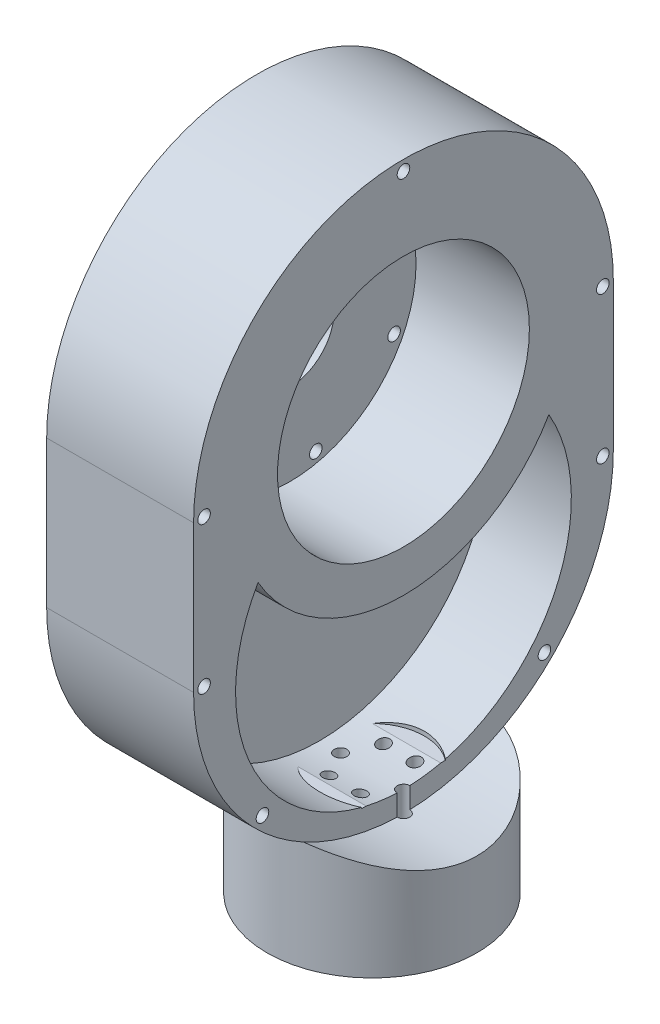
SolidWorks part; units mm, degrees
material "ABS"
ref_plane "Alzado" through (0, 0, 0) normal (0, 0, 1) x (1, 0, 0)
ref_plane "Planta" through (0, 0, 0) normal (0, 1, 0) x (1, 0, 0)
ref_plane "Vista lateral" through (0, 0, 0) normal (1, 0, 0) x (0, 0, -1)
sketch "Croquis3" plane through (0, 0, 0) normal (1, 0, 0) x (0, 0, -1)
  line L0 (-50, 105) -> (-50, 70)
  line L1 (50, 70) -> (50, 105)
  arc A0 (50, 105) -> (-50, 105) centre (0, 105) ccw
  arc A1 (-50, 70) -> (50, 70) centre (0, 70) ccw
  dimension "D1" = 100
  dimension "D3" = 35
  dimension "D4" = 70
extrude "Saliente-Extruir3" add sketch "Croquis3" along normal mid plane 55
sketch "Croquis2" plane through (0, 0, 0) normal (0, 1, 0) x (1, 0, 0)
  circle A0 centre (0, 0) radius 25
  dimension "D1" = 50
extrude "Saliente-Extruir4" add sketch "Croquis2" along normal up to next
sketch "Croquis5" plane through (-27.5, 0, 0) normal (-1, 0, 0) x (0, 0, 1)
  circle A0 centre (0, 105) radius 45
  circle A1 centre (0, 105) radius 32.5
  dimension "D1" = 90
  dimension "D2" = 65
extrude "Cortar-Extruir2" cut sketch "Croquis5" against normal blind 2.5
sketch "Croquis6" plane through (-27.5, 0, 0) normal (-1, 0, 0) x (0, 0, 1)
  circle A0 centre (0, 105) radius 10.5
  dimension "D1" = 21
extrude "Cortar-Extruir3" cut sketch "Croquis6" against normal through all
sketch "Croquis7" plane through (27.5, 0, 0) normal (1, 0, 0) x (0, 0, -1)
  line L2 (-50, 105) -> (-50, 70)
  line L3 (50, 70) -> (50, 105)
  line L4 (-50, 105) -> (-50, 70)
  line L5 (50, 70) -> (50, 105)
  arc A2 (50, 105) -> (-50, 105) centre (0, 105) ccw
  arc A3 (-50, 70) -> (50, 70) centre (0, 70) ccw
  arc A4 (50, 105) -> (-50, 105) centre (0, 105) ccw
  arc A5 (-50, 70) -> (50, 70) centre (0, 70) ccw
  dimension "D1" = 0
extrude "Cortar-Extruir4" cut sketch "Croquis7" against normal blind 20
sketch "Croquis8" plane through (7.5, 0, 0) normal (1, 0, 0) x (0, 0, -1)
  circle A0 centre (0, 105) radius 30
  dimension "D1" = 60
extrude "Cortar-Extruir5" cut sketch "Croquis8" against normal blind 27
sketch "Croquis9" plane through (0, 0, 0) normal (0, -1, 0) x (1, 0, 0)
  circle A6 centre (0, 0) radius 7.5 construction
  circle A7 centre (7.5, 0) radius 1.5
  circle A8 centre (3.75, -6.4952) radius 1.5
  circle A9 centre (-3.75, -6.4952) radius 1.5
  circle A10 centre (-7.5, 0) radius 1.5
  circle A11 centre (-3.75, 6.4952) radius 1.5
  circle A12 centre (3.75, 6.4952) radius 1.5
  point P17 (0, 0)
  dimension "D2" = 3
  dimension "D1" = 15
extrude "Cortar-Extruir7" cut sketch "Croquis9" against normal blind 30
ref_plane "Plano1" through (0, 26, 0) normal (0, 1, 0) x (1, 0, 0)
sketch "Croquis10" plane through (0, 26, 0) normal (0, 1, 0) x (1, 0, 0)
  circle A0 centre (0, 0) radius 12.5
  dimension "D1" = 25
extrude "Cortar-Extruir8" cut sketch "Croquis10" along normal blind 5
sketch "Croquis11" plane through (-27.5, 0, 0) normal (-1, 0, 0) x (0, 0, 1)
  circle A0 centre (0, 105) radius 27.5 construction
  circle A1 centre (27.5, 105) radius 1.5
  circle A2 centre (17.146, 83.4996) radius 1.5
  circle A3 centre (-6.1193, 78.1895) radius 1.5
  circle A4 centre (-24.7766, 93.0682) radius 1.5
  circle A5 centre (-24.7766, 116.9318) radius 1.5
  circle A6 centre (-6.1193, 131.8105) radius 1.5
  circle A7 centre (17.146, 126.5004) radius 1.5
  point P20 (0, 105)
  dimension "D1" = 3
  dimension "D2" = 7
extrude "Cortar-Extruir9" cut sketch "Croquis11" against normal through all
sketch "Croquis12" plane through (7.5, 0, 0) normal (1, 0, 0) x (0, 0, -1)
  line L0 (-1.5, 0) -> (1.5, 0) construction
  arc A0 (-34.641, 85) -> (34.641, 85) centre (0, 65) ccw
  arc A1 (-34.641, 85) -> (34.641, 85) centre (0, 105) ccw
  dimension "D1" = 80
  dimension "D3" = 80
  dimension "D2" = 65
extrude "Cortar-Extruir10" cut sketch "Croquis12" against normal blind 20
sketch "Croquis13" plane through (7.5, 0, 0) normal (1, 0, 0) x (0, 0, -1)
  circle A0 centre (0, 152.5) radius 1.5
  circle A1 centre (0, 105) radius 47.5 construction
  circle A2 centre (47.5, 105) radius 1.5
  circle A3 centre (0, 57.5) radius 1.5 construction
  circle A4 centre (-47.5, 105) radius 1.5
  circle A5 centre (0, 70) radius 47.5 construction
  circle A6 centre (-47.5, 70) radius 1.5
  circle A7 centre (-33.5876, 103.5876) radius 1.5 construction
  circle A8 centre (0, 117.5) radius 1.5 construction
  circle A9 centre (33.5876, 103.5876) radius 1.5 construction
  circle A10 centre (47.5, 70) radius 1.5
  circle A11 centre (33.5876, 36.4124) radius 1.5
  circle A12 centre (0, 22.5) radius 1.5 construction
  circle A13 centre (-33.5876, 36.4124) radius 1.5
  point P14 (0, 105)
  point P33 (0, 70)
  dimension "D1" = 95
  dimension "D3" = 3
  dimension "D4" = 95
  dimension "D5" = 3
  dimension "D2" = 4
  dimension "D6" = 8
extrude "Cortar-Extruir11" cut sketch "Croquis13" against normal through all
sketch "Croquis14" plane through (0, 0, 0) normal (0, -1, 0) x (1, 0, 0)
  circle A0 centre (0, 0) radius 17.5
  circle A1 centre (0, 0) radius 10
  dimension "D1" = 35
  dimension "D2" = 20
extrude "Cortar-Extruir12" cut sketch "Croquis14" against normal blind 2
sketch "Croquis15" plane through (-27.5, 0, 0) normal (-1, 0, 0) x (0, 0, 1)
  circle A0 centre (0, 105) radius 13.5
  circle A1 centre (0, 105) radius 10
  dimension "D1" = 27
  dimension "D2" = 20
extrude "Cortar-Extruir13" cut sketch "Croquis15" against normal blind 4
